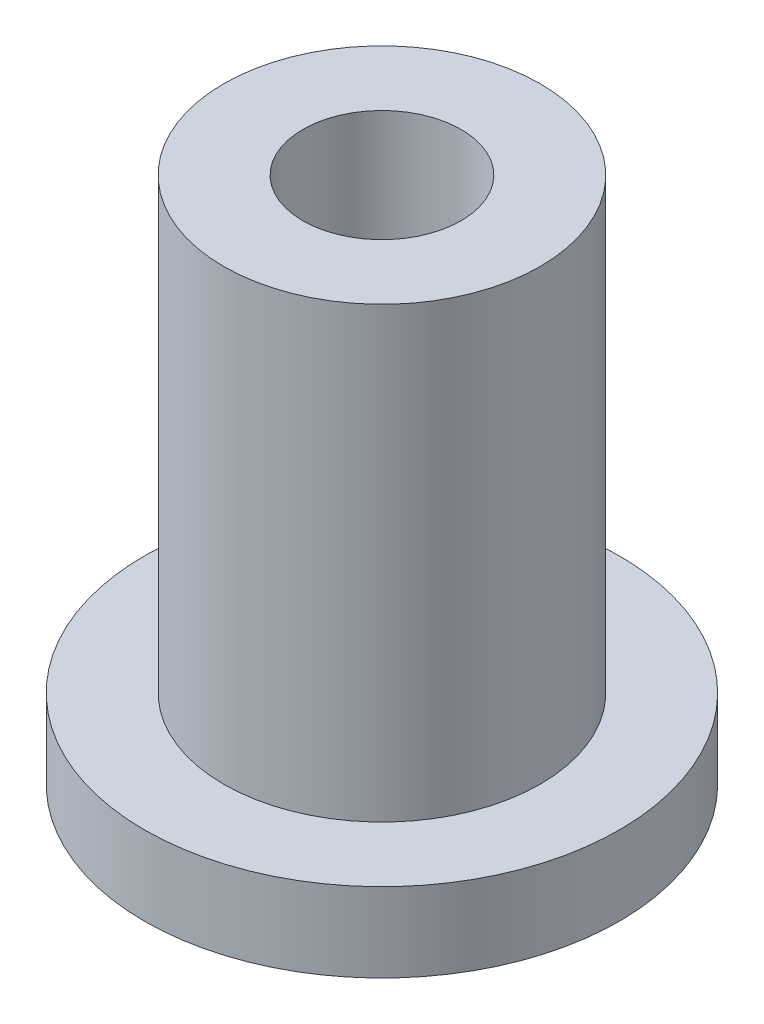
SolidWorks part; units mm, degrees
material "latón"
ref_plane "Alzado" through (0, 0, 0) normal (0, 0, 1) x (1, 0, 0)
ref_plane "Planta" through (0, 0, 0) normal (0, 1, 0) x (1, 0, 0)
ref_plane "Vista lateral" through (0, 0, 0) normal (1, 0, 0) x (0, 0, -1)
sketch "Croquis1" plane through (0, 0, 0) normal (0, 1, 0) x (1, 0, 0)
  circle A0 centre (0, 0) radius 4.5
  circle A1 centre (0, 0) radius 1.5
  dimension "D1" = 3
  dimension "D2" = 9
extrude "Saliente-Extruir1" add sketch "Croquis1" along normal blind 1.5
sketch "Croquis2" plane through (0, 1.5, 0) normal (0, 1, 0) x (1, 0, 0)
  circle A0 centre (0, 0) radius 1.5
  circle A1 centre (0, 0) radius 3
  dimension "D1" = 3
  dimension "D2" = 6
extrude "Saliente-Extruir2" add sketch "Croquis2" along normal blind 8.5
